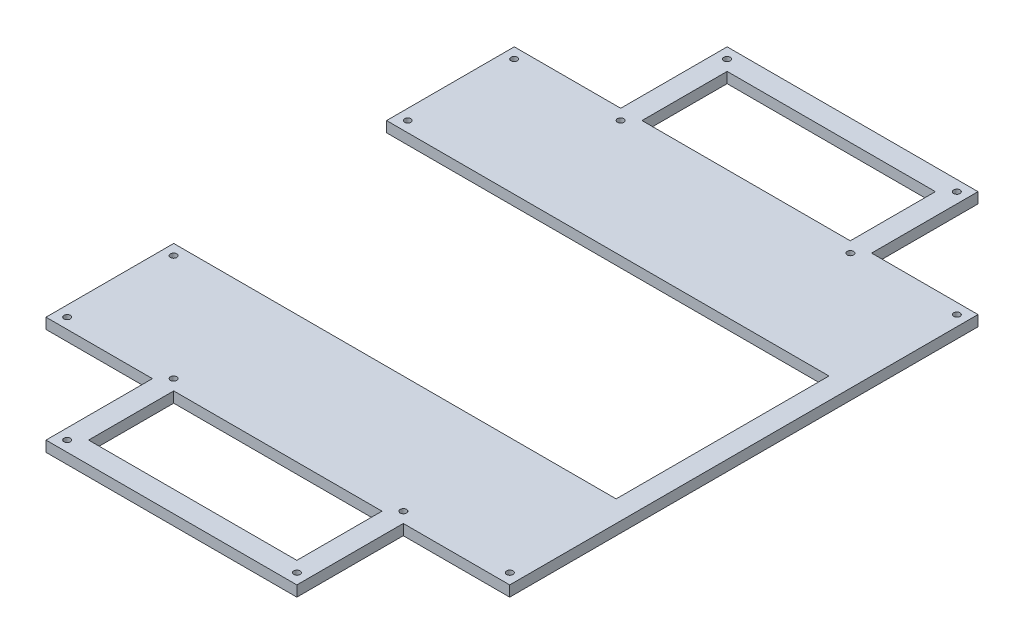
SolidWorks part; units mm, degrees
ref_plane "Plan de face" through (0, 0, 0) normal (0, 0, 1) x (1, 0, 0)
ref_plane "Plan de dessus" through (0, 0, 0) normal (0, 1, 0) x (1, 0, 0)
ref_plane "Plan de droite" through (0, 0, 0) normal (1, 0, 0) x (0, 0, -1)
sketch "Esquisse1" plane through (0, 0, 0) normal (0, 1, 0) x (1, 0, 0)
  line L0 (-58.9276, 110) -> (-58.9276, 160)
  line L1 (108.9276, -110) -> (58.9276, -110)
  line L2 (108.9276, -110) -> (108.9276, 110)
  line L3 (108.9276, 110) -> (58.9276, 110)
  line L4 (-108.9276, -110) -> (-108.9276, -50)
  line L5 (108.9276, -110) -> (-108.9276, 110) construction
  line L6 (108.9276, 110) -> (-108.9276, -110) construction
  line L7 (-58.9276, 160) -> (58.9276, 160)
  line L8 (58.9276, 160) -> (58.9276, 110)
  line L9 (0, 160) -> (0, -89.8749) construction
  line L10 (-108.9276, 0) -> (108.9276, 0) construction
  line L11 (-103.9763, -105) -> (-103.9763, -50) construction
  line L12 (-53.9763, -105) -> (-53.9763, -160) construction
  line L13 (-58.9276, 110) -> (-108.9276, 110)
  line L14 (58.9276, -160) -> (58.9276, -110)
  line L15 (-58.9276, -160) -> (58.9276, -160)
  line L16 (-58.9276, -110) -> (-58.9276, -160)
  line L17 (-58.9276, -110) -> (-108.9276, -110)
  line L18 (48.9276, -150) -> (-48.9276, -150)
  line L19 (48.9276, 110) -> (-48.9276, 110)
  line L20 (48.9276, 110) -> (48.9276, 150)
  line L21 (48.9276, 150) -> (-48.9276, 150)
  line L22 (-48.9276, 110) -> (-48.9276, 150)
  line L23 (48.9276, 110) -> (-48.9276, 150) construction
  line L24 (48.9276, 150) -> (-48.9276, 110) construction
  line L25 (-48.9276, -110) -> (-48.9276, -150)
  line L26 (48.9276, -110) -> (-48.9276, -110)
  line L27 (48.9276, -110) -> (48.9276, -150)
  line L28 (-108.9276, 50) -> (-108.9276, 110)
  line L29 (98.9276, -50) -> (-108.9276, -50)
  line L30 (98.9276, -50) -> (98.9276, 50)
  line L31 (98.9276, 50) -> (-108.9276, 50)
  line L33 (-103.9763, -105) -> (103.9763, -105) construction
  line L34 (103.9763, -105) -> (103.9763, 0) construction
  circle A0 centre (-103.9763, -105) radius 1.5
  circle A1 centre (-103.9763, -55) radius 1.5
  circle A2 centre (-53.9763, -105) radius 1.5
  circle A5 centre (-3.9763, -105) radius 1.5 [skipped]
  circle A6 centre (46.0237, -105) radius 1.5 [skipped]
  circle A7 centre (-53.9763, -155) radius 1.5
  circle A8 centre (-53.9763, 155) radius 1.5
  circle A9 centre (-53.9763, 105) radius 1.5
  circle A10 centre (-103.9763, 105) radius 1.5
  circle A11 centre (-103.9763, 55) radius 1.5
  circle A12 centre (53.9763, -155) radius 1.5
  circle A13 centre (53.9763, -105) radius 1.5
  circle A14 centre (103.9763, -105) radius 1.5
  circle A15 centre (103.9763, 105) radius 1.5
  circle A16 centre (53.9763, 105) radius 1.5
  circle A17 centre (53.9763, 155) radius 1.5
  point P0 (0, 0)
  point P23 (0, 130)
  point P28 (-48.9276, 130)
  point P33 (0, 0)
  dimension "D4" = 3
  dimension "D6" = 50
  dimension "D14" = 5
  dimension "D16" = 5
  dimension "D1" = 220
  dimension "D2" = 50
  dimension "D3" = 50
  dimension "D5" = 5
  dimension "D7" = 30
  dimension "D8" = 10
  dimension "D9" = 10
  dimension "D10" = 10
  dimension "D11" = 60
  dimension "D13" = 2
  dimension "D12" = 60
  dimension "D15" = 4
  dimension "D17" = 2
extrude "Boss.-Extru.1" add sketch "Esquisse1" along normal blind 5
